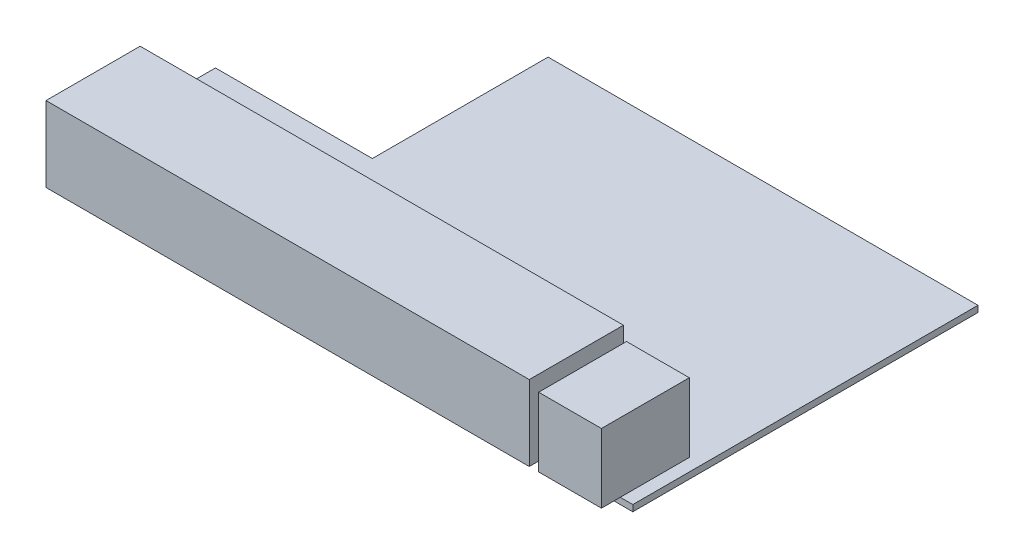
SolidWorks part; units mm, degrees
ref_plane "Front Plane" through (0, 0, 0) normal (0, 0, 1) x (1, 0, 0)
ref_plane "Top Plane" through (0, 0, 0) normal (0, 1, 0) x (1, 0, 0)
ref_plane "Right Plane" through (0, 0, 0) normal (1, 0, 0) x (0, 0, -1)
sketch "Sketch1" plane through (0, 0, 0) normal (0, 1, 0) x (1, 0, 0)
  line L0 (-46.967, -0.6277) -> (-21.967, -0.6277)
  line L1 (-21.967, 27.3723) -> (46.533, 27.3723)
  line L2 (-46.967, -0.6277) -> (-46.967, -27.6277)
  line L3 (-46.967, -27.6277) -> (46.533, -27.6277)
  line L4 (46.533, 27.3723) -> (46.533, -27.6277)
  line L5 (-21.967, 13.0423) -> (46.533, -27.6277) construction
  line L6 (-46.967, -27.6277) -> (46.533, 27.3723) construction
  line L7 (-21.967, -0.6277) -> (-21.967, 27.3723)
  point P4 (0, 0)
  dimension "D1" = 55
  dimension "D2" = 93.5
  dimension "D3" = 25
  dimension "D4" = 28
extrude "Boss-Extrude1" add sketch "Sketch1" along normal blind 1 contours L1 L4 L3 L2 L0 L7
sketch "Sketch2" plane through (0, 1, 0) normal (0, 1, 0) x (1, 0, 0)
  line L0 (-46.967, -0.6277) -> (-46.967, -27.6277) construction
  line L1 (-43.967, -15.6277) -> (33.033, -15.6277)
  line L2 (-43.967, -15.6277) -> (-43.967, -30.6277)
  line L3 (-43.967, -30.6277) -> (33.033, -30.6277)
  line L4 (33.033, -15.6277) -> (33.033, -30.6277)
  line L5 (-43.967, -15.6277) -> (33.033, -30.6277) construction
  line L6 (-43.967, -30.6277) -> (33.033, -15.6277) construction
  line L8 (-46.967, -27.6277) -> (46.533, -27.6277) construction
  point P4 (-5.467, -23.1277)
  dimension "D1" = 15
  dimension "D2" = 77
  dimension "D3" = 3
  dimension "D4" = 3
extrude "Boss-Extrude2" add sketch "Sketch2" along normal blind 12
sketch "Sketch3" plane through (0, 1, 0) normal (0, 1, 0) x (1, 0, 0)
  line L0 (46.533, 27.3723) -> (46.533, -27.6277) construction
  line L1 (34.533, -16.6277) -> (44.533, -16.6277)
  line L2 (34.533, -16.6277) -> (34.533, -30.6277)
  line L3 (34.533, -30.6277) -> (44.533, -30.6277)
  line L4 (44.533, -16.6277) -> (44.533, -30.6277)
  line L5 (34.533, -16.6277) -> (44.533, -30.6277) construction
  line L6 (34.533, -30.6277) -> (44.533, -16.6277) construction
  line L7 (-43.967, -30.6277) -> (33.033, -30.6277) construction
  line L8 (33.033, -15.6277) -> (-43.967, -15.6277) construction
  point P4 (39.533, -23.6277)
  dimension "D1" = 10
  dimension "D2" = 2
  dimension "D3" = 1
extrude "Boss-Extrude3" add sketch "Sketch3" along normal blind 11
